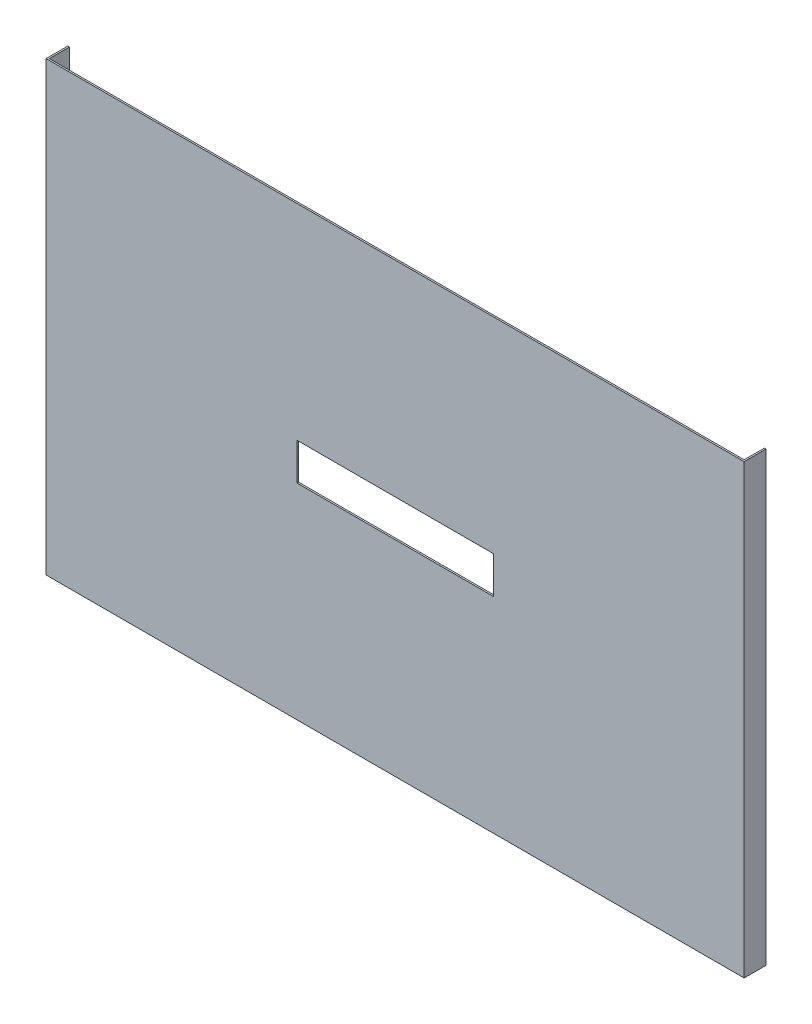
SolidWorks part; units mm, degrees
ref_plane "Front Plane" through (0, 0, 0) normal (0, 0, 1) x (1, 0, 0)
ref_plane "Top Plane" through (0, 0, 0) normal (0, 1, 0) x (1, 0, 0)
ref_plane "Right Plane" through (0, 0, 0) normal (1, 0, 0) x (0, 0, -1)
other "Configuration Table"
sketch "Sketch1" plane through (0, 0, 0) normal (0, 1, 0) x (1, 0, 0)
  line L0 (30, -40) -> (30, -20)
  line L1 (30, -20) -> (31.5, -20)
  line L2 (31.5, -20) -> (31.5, -38.5)
  line L3 (31.5, -38.5) -> (668.5, -38.5)
  line L4 (668.5, -38.5) -> (668.5, -20)
  line L5 (668.5, -20) -> (670, -20)
  line L6 (670, -20) -> (670, -40)
  line L7 (670, -40) -> (30, -40)
extrude "TOPPING_klape_kat3_kapak_1" add sketch "Sketch1" along normal blind 410 from offset 740 separate body
sketch "Sketch2" plane through (0, 0, 0) normal (0, 0, 1) x (1, 0, 0)
  line L1 (260, 928) -> (440, 928)
  line L2 (260, 928) -> (260, 962)
  line L3 (260, 962) -> (440, 962)
  line L4 (440, 928) -> (440, 962)
extrude "TOPPING_klape_kat3_kapak_2" cut sketch "Sketch2" along normal blind 14 from offset 27
